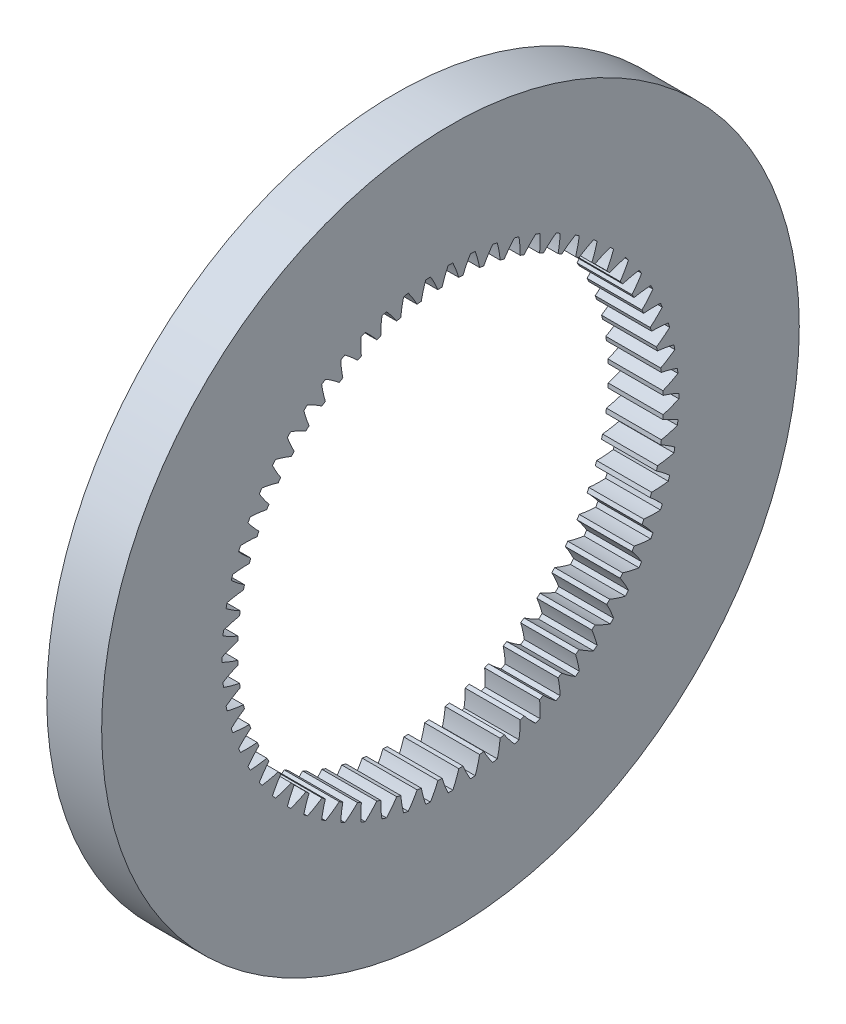
SolidWorks part; units mm, degrees
ref_plane "Plane1" through (0, 0, 0) normal (0, 0, 1) x (1, 0, 0)
ref_plane "Plane2" through (0, 0, 0) normal (0, 1, 0) x (1, 0, 0)
ref_plane "Plane3" through (0, 0, 0) normal (1, 0, 0) x (0, 0, -1)
other "Configuration Table"
sketch "HoldingSke" plane through (0, 0, 0) normal (0, 1, 0) x (1, 0, 0)
  line L0 (0, 0) -> (0.3507, -0.719)
  line L1 (-15, 0) -> (100, 0) construction
  line L2 (0, 0) -> (-2.1039, 2.3779)
  line L3 (0, 0) -> (-11.863, 4.5341)
  line L4 (0, 0) -> (3.7858, 7.762)
  line L5 (0, 0) -> (-23.7986, -8.8762)
  line L6 (0, 0) -> (-10.5278, -7.1032)
  line L7 (-2.1039, 2.3779) -> (3.3635, 27.1825)
  line L8 (-76.2, 3.6279) -> (-54.61, 3.6279)
  line L9 (-71.009, 38.7566) -> (-53.1078, 45.2721)
  line L10 (-76.2, 71.12) -> (104.1128, 71.12)
  line L11 (0, 0) -> (-20, 0)
  line L12 (-76.2, 101.6) -> (-76.155, 101.6)
  line L13 (24.9733, 27.94) -> (52.9518, 28.4284)
  line L14 (24.9733, 27.94) -> (24.9743, 27.94)
  line L15 (24.9733, 27.94) -> (100.4006, 29.5858)
  circle A0 centre (0, 0) radius 50
  circle A1 centre (0, 0) radius 12.7
  circle A2 centre (0, 0) radius 12.7
  dimension "MHD" = 25.4
  dimension "Hub_dia" = 25.4
  dimension "Diameter" = 100
  dimension "Num_teeth" = 64
  dimension "Pitch" = 0.8
  dimension "Overall_len" = 25.4
  dimension "Show_teeth" = 64
  dimension "Thickness" = 12.7
  dimension "OAL" = 25.4001
  dimension "T_dim" = 21.59
  dimension "Ap" = 20
  dimension "H" = 19.05
  dimension "Pitch_radius" = 180.3128
  dimension "Width" = 20
  dimension "Backlash" = 0.045
  dimension "Addendum_fac" = 1
  dimension "Dedendum_fac" = 1.25
  dimension "Clearance_fac" = 0.25
  dimension "Dedendum_add" = 0.001
  dimension "Module" = 1.25
sketch "BasProSke" plane through (0, 0, 0) normal (0, 1, 0) x (1, 0, 0)
  line L0 (-10, 0) -> (60, 0) construction
  line L1 (0, 38.75) -> (0, 50)
  line L2 (0, 38.75) -> (20, 38.75)
  line L3 (20, 38.75) -> (20, 50)
  line L4 (20, 50) -> (0, 50)
  dimension "Diameter" = 100
  dimension "Thickness" = 20
  dimension "Inside_diameter" = 77.5
revolve "Base-Revolve" add sketch "BasProSke" angle 360 about L0
sketch "TooCutSke" plane through (0, 0, 0) normal (1, 0, 0) x (0, 0, -1)
  line L3 (1.0941, 39.985) -> (1.0941, 53.6633) construction
  line L4 (0, 0) -> (0, 59.563) construction
  line L5 (0, 0) -> (-3.3527, 68.2452) construction
  line L6 (-17.6475, 33.0028) -> (36.1373, 35.645) construction
  circle A0 centre (0, 0) radius 40 construction
  circle A1 centre (0, 0) radius 41.5635 construction
  circle A2 centre (0, 0) radius 33.8289 construction
  circle A3 centre (0, 0) radius 38.7246 construction
  arc A4 (1.5255, 38.6945) -> (0.4288, 41.5613) centre (-17.6475, 33.0028) ccw
  arc A5 (1.5255, 38.6945) -> (-1.5255, 38.6945) centre (0, 0) ccw
  arc A6 (0.4288, 41.5613) -> (-0.4288, 41.5613) centre (0, 0) ccw
  arc A7 (-0.4288, 41.5613) -> (-1.5255, 38.6945) centre (17.6475, 33.0028) ccw
  dimension "Pitch_dia" = 80
  dimension "Base_dia" = 67.6579
  dimension "Root_dia" = 83.127
  dimension "Overcut_dia" = 77.4492
  dimension "Flank_rad" = 20
  dimension "Half_ang" = 2.813
  dimension "Half_CT" = 1.0941
extrude "ToothCut" cut sketch "TooCutSke" along normal through all
fillet "Breaks" [suppressed] radius 0.125
fillet "RootFillets" [suppressed] radius 0.3135
pattern_circular "TeethCuts" count 64 every 5.625 about axis through (-10, 0, 0) along (1, 0, 0) of "RootFillets", "Breaks", "ToothCut"
sketch "Sketch1" plane through (20, 0, 0) normal (1, 0, 0) x (0, 0, -1)
  circle A0 centre (0, 0) radius 63.5
  circle A1 centre (0, 0) radius 50
  dimension "D1" = 127
extrude "Boss-Extrude1" add sketch "Sketch1" against normal blind 10
sketch "Sketch3" plane through (10, 0, 0) normal (-1, 0, 0) x (0, 0, 1)
  circle A0 centre (0, 0) radius 63.5
extrude "Cut-Extrude2" cut sketch "Sketch3" along normal blind 20
equation "' \"Module@HoldingSke\" = 6.35"
equation "' \"Num_teeth@HoldingSke\" = 24"
equation "' \"Ap@HoldingSke\" =  14.5"
equation "' \"Ap@HoldingSke\" = 14.5"
equation "' \"Width@HoldingSke\" = 12"
equation "' \"Diameter@HoldingSke\" = 8 * 25.4"
equation "' \"Show_teeth@HoldingSke\" = 100"
equation "' \"Backlash@HoldingSke\" = 0.009 * 25.4"
equation "' \"Addendum_fac@HoldingSke\" = 1.0"
equation "' \"Dedendum_fac@HoldingSke\" = 1.25"
equation "' \"Dedendum_add@HoldingSke\" = 0.00005 * 25.4"
equation "' \"Clearance_fac@HoldingSke\" = 0.25"
equation "\"Pitch@HoldingSke\" = 1 / \"Module@HoldingSke\" "
equation "\"Overcut_dia@TooCutSke\" = (\"Num_teeth@HoldingSke\" - 2 * \"Addendum_fac@HoldingSke\") / \"Pitch@HoldingSke\" - 0.002 * 25.4"
equation "\"Pitch_dia@TooCutSke\" = \"Num_teeth@HoldingSke\" / \"Pitch@HoldingSke\""
equation "\"Base_dia@TooCutSke\" = \"Num_teeth@HoldingSke\" / \"Pitch@HoldingSke\" * cos((\"Ap@HoldingSke\"  * 3.14159265 / 180)) * 0.90"
equation "\"Root_dia@TooCutSke\" = \"Num_teeth@HoldingSke\"  / \"Pitch@HoldingSke\" + 2 *  \"Dedendum_fac@HoldingSke\"/ \"Pitch@HoldingSke\" + \"Dedendum_add@HoldingSke\" * 2"
equation "\"Half_ang@TooCutSke\" = 180 / \"Num_teeth@HoldingSke\""
equation "\"Half_CT@TooCutSke\" = \"Num_teeth@HoldingSke\" / \"Pitch@HoldingSke\" * sin((3.14159265 / 2 / \"Num_teeth@HoldingSke\")) / 2 + 10 * \"Backlash@HoldingSke\" / 4"
equation "\"Flank_rad@TooCutSke\" = \"Num_teeth@HoldingSke\" / \"Pitch@HoldingSke\" / 4"
equation "\"Radius@RootFillets\"= \"Clearance_fac@HoldingSke\" / \"Pitch@HoldingSke\" + \"Dedendum_add@HoldingSke\""
equation "\"Break_rad@Breaks\" = 0.02 / \"Pitch@HoldingSke\" * 5"
equation "\"Num_teeth@TeethCuts\" = int( \"Show_teeth@HoldingSke\" ) + 1"
equation "\"Num_teeth@TeethCuts\" = ((sgn( \"Num_teeth@TeethCuts\" - \"Num_teeth@HoldingSke\" )-1)*( \"Num_teeth@TeethCuts\" - \"Num_teeth@HoldingSke\" ))/-2+ \"Num_teeth@HoldingSke\""
equation "\"Num_teeth@TeethCuts\" = ((sgn( \"Num_teeth@TeethCuts\" - 2.0)+1)*( \"Num_teeth@TeethCuts\" - 2.0))/2 +2.0"
equation "\"Angle@TeethCuts\" = 360.0 / \"Num_teeth@HoldingSke\""
equation "\"Diameter@BasProSke\" = \"Num_teeth@HoldingSke\"  / \"Pitch@HoldingSke\" + 2 *  \"Dedendum_fac@HoldingSke\"/ \"Pitch@HoldingSke\" + \"Dedendum_add@HoldingSke\" * 2 + 0.002 * 25.4"
equation "\"Diameter@BasProSke\" = ((sgn( \"Diameter@BasProSke\"  - \"Diameter@HoldingSke\" )+1)*( \"Diameter@BasProSke\"  - \"Diameter@HoldingSke\" ))/2 + \"Diameter@HoldingSke\""
equation "\"Inside_diameter@BasProSke\" =  (\"Num_teeth@HoldingSke\" - 2 * \"Addendum_fac@HoldingSke\") / \"Pitch@HoldingSke\" "
equation "\"Thickness@BasProSke\"  = \"Width@HoldingSke\""
